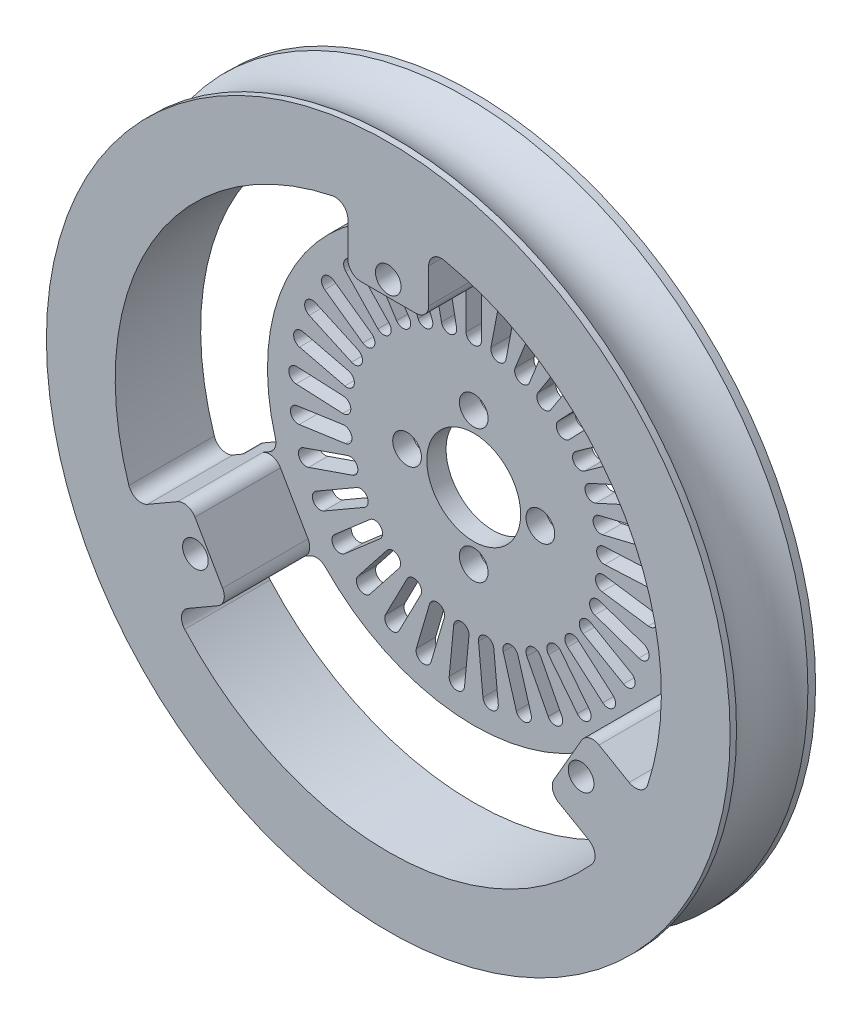
SolidWorks part; units mm, degrees
ref_plane "Plan de face" through (0, 0, 0) normal (0, 0, 1) x (1, 0, 0)
ref_plane "Plan de dessus" through (0, 0, 0) normal (0, 1, 0) x (1, 0, 0)
ref_plane "Plan de droite" through (0, 0, 0) normal (1, 0, 0) x (0, 0, -1)
sketch "Esquisse1" plane through (0, 0, 0) normal (0, 0, 1) x (1, 0, 0)
  circle A0 centre (0, 0) radius 33.8667
  dimension "D1" = 67.7333
extrude "Boss.-Extru.1" add sketch "Esquisse1" along normal blind 8.4667
sketch "Esquisse2" plane through (0, 0, 8.4667) normal (0, 0, 1) x (1, 0, 0)
  line L0 (4.0005, 25.2365) -> (4.0005, 21.8006)
  line L1 (2.7305, 20.5306) -> (-2.7305, 20.5306)
  line L2 (-4.0005, 21.8006) -> (-4.0005, 25.2365)
  line L3 (20.8801, -7.4357) -> (23.8557, -9.1537)
  line L4 (16.4147, -12.63) -> (19.1452, -7.9006)
  line L5 (19.8552, -16.0828) -> (16.8796, -14.3648)
  line L6 (-16.8796, -14.3648) -> (-19.8552, -16.0828)
  line L7 (-19.1452, -7.9006) -> (-16.4147, -12.63)
  line L8 (-23.8557, -9.1537) -> (-20.8801, -7.4357)
  arc A0 (-5.5301, 26.4797) -> (-25.6972, -8.4506) centre (0, 0) ccw
  arc A1 (4.0005, 21.8006) -> (2.7305, 20.5306) centre (2.7305, 21.8006) cw
  arc A2 (-2.7305, 20.5306) -> (-4.0005, 21.8006) centre (-2.7305, 21.8006) cw
  arc A3 (4.0005, 25.2365) -> (5.5301, 26.4797) centre (5.2705, 25.2365) cw
  arc A4 (-4.0005, 25.2365) -> (-5.5301, 26.4797) centre (-5.2705, 25.2365) ccw
  arc A5 (19.1452, -7.9006) -> (20.8801, -7.4357) centre (20.2451, -8.5356) cw
  arc A6 (16.8796, -14.3648) -> (16.4147, -12.63) centre (17.5146, -13.265) cw
  arc A7 (19.8552, -16.0828) -> (20.167, -18.0291) centre (19.2202, -17.1826) cw
  arc A8 (23.8557, -9.1537) -> (25.6972, -8.4506) centre (24.4907, -8.0539) ccw
  arc A9 (-16.4147, -12.63) -> (-16.8796, -14.3648) centre (-17.5146, -13.265) cw
  arc A10 (-20.8801, -7.4357) -> (-19.1452, -7.9006) centre (-20.2451, -8.5356) cw
  arc A11 (-23.8557, -9.1537) -> (-25.6972, -8.4506) centre (-24.4907, -8.0539) cw
  arc A12 (-19.8552, -16.0828) -> (-20.167, -18.0291) centre (-19.2202, -17.1826) ccw
  arc A13 (-20.167, -18.0291) -> (20.167, -18.0291) centre (0, 0) ccw
  arc A14 (25.6972, -8.4506) -> (5.5301, 26.4797) centre (0, 0) ccw
  point P5 (0, 20.5306)
  point P9 (4.0005, 20.5306)
  point P12 (-4.0005, 20.5306)
  point P15 (4.0005, 26.7536)
  point P45 (0, 0)
  dimension "D1" = 54.102
  dimension "D4" = 1.27
  dimension "D5" = 1.27
  dimension "D2" = 8.001
  dimension "D3" = 6.223
  dimension "D6" = 3
extrude "Enlèv. mat.-Extru.1" cut sketch "Esquisse2" against normal up to next
sketch "Esquisse7" plane through (0, 0, 0) normal (0, 1, 0) x (1, 0, 0)
  line L0 (0, -31.0899) -> (0, 31.0899) construction
  line L1 (-33.8667, 0) -> (-33.8667, -8.4667) construction
  line L2 (-33.8667, -0.762) -> (-33.8667, -7.8317)
  arc A0 (-33.8667, -7.8317) -> (-33.8667, -0.762) centre (-38.151, -4.2968) ccw
  point P0 (-32.5967, -4.2968)
  point P13 (0, 0)
  dimension "D1" = 0.635
  dimension "D2" = 1.27
  dimension "D3" = 0.762
revolve "Enlèvement de matière-Révolution4" cut sketch "Esquisse7" angle 360 about L0
sketch "Esquisse8" plane through (0, 0, 0) normal (0, 0, 1) x (1, 0, 0)
  line L0 (-22.7559, -8.5187) -> (-20.2341, -7.0628)
  line L1 (-18.7554, -15.4478) -> (-16.2336, -13.9919)
  line L2 (-16.4147, -12.63) -> (-19.1452, -7.9006) construction
  line L3 (-20.4902, -14.9829) -> (-23.2207, -10.2536)
  line L4 (4.0005, 23.9665) -> (4.0005, 21.0547)
  line L5 (-4.0005, 23.9665) -> (-4.0005, 21.0547)
  line L6 (-2.7305, 25.2365) -> (2.7305, 25.2365)
  line L7 (22.7559, -8.5187) -> (20.2341, -7.0628)
  line L8 (18.7554, -15.4478) -> (16.2336, -13.9919)
  line L9 (23.2207, -10.2536) -> (20.4902, -14.9829)
  line L10 (19.1452, -7.9006) -> (16.4147, -12.63) construction
  line L11 (-2.7305, 20.5306) -> (2.7305, 20.5306) construction
  arc A0 (-4.9621, 19.8227) -> (-19.648, -5.614) centre (0, 0) ccw
  arc A1 (-14.6859, -14.2086) -> (14.6859, -14.2086) centre (0, 0) ccw
  arc A2 (19.648, -5.614) -> (4.9621, 19.8227) centre (0, 0) ccw
  arc A3 (4.0005, 21.0547) -> (4.9621, 19.8227) centre (5.2705, 21.0547) ccw
  arc A4 (-4.0005, 21.0547) -> (-4.9621, 19.8227) centre (-5.2705, 21.0547) cw
  arc A5 (-20.2341, -7.0628) -> (-19.648, -5.614) centre (-20.8691, -5.9629) ccw
  arc A6 (-16.2336, -13.9919) -> (-14.6859, -14.2086) centre (-15.5986, -15.0917) cw
  arc A7 (16.2336, -13.9919) -> (14.6859, -14.2086) centre (15.5986, -15.0917) ccw
  arc A8 (20.2341, -7.0628) -> (19.648, -5.614) centre (20.8691, -5.9629) cw
  arc A9 (22.7559, -8.5187) -> (23.2207, -10.2536) centre (22.1209, -9.6186) cw
  arc A10 (18.7554, -15.4478) -> (20.4902, -14.9829) centre (19.3904, -14.3479) ccw
  arc A11 (-18.7554, -15.4478) -> (-20.4902, -14.9829) centre (-19.3904, -14.3479) cw
  arc A12 (-22.7559, -8.5187) -> (-23.2207, -10.2536) centre (-22.1209, -9.6186) ccw
  arc A13 (-4.0005, 23.9665) -> (-2.7305, 25.2365) centre (-2.7305, 23.9665) cw
  arc A14 (4.0005, 23.9665) -> (2.7305, 25.2365) centre (2.7305, 23.9665) ccw
  point P34 (-15.3539, -13.484)
  point P37 (15.3539, -13.484)
  point P40 (19.3544, -6.5549)
  point P43 (23.8557, -9.1537)
  point P46 (19.8552, -16.0828)
  point P49 (-19.8552, -16.0828)
  point P52 (-23.8557, -9.1537)
  point P55 (-4.0005, 25.2365)
  point P58 (4.0005, 25.2365)
  dimension "D1" = 20.4343
  dimension "D2" = 1.27
extrude "Boss.-Extru.2" add sketch "Esquisse8" against normal blind 1.905
sketch "Esquisse9" plane through (0, 0, -1.905) normal (0, 0, -1) x (-1, 0, 0)
  circle A0 centre (0, 0) radius 4.6482
  dimension "D1" = 9.2964
extrude "Enlèv. mat.-Extru.5" cut sketch "Esquisse9" against normal through all
sketch "Esquisse10" plane through (0, 0, 0) normal (0, 0, 1) x (1, 0, 0)
  circle A0 centre (0, 6.604) radius 1.4224
  circle A1 centre (6.604, 0) radius 1.4224
  circle A2 centre (0, -6.604) radius 1.4224
  circle A3 centre (-6.604, 0) radius 1.4224
  point P12 (0, 0)
  dimension "D1" = 2.8448
  dimension "D2" = 6.604
  dimension "D3" = 4
extrude "Enlèv. mat.-Extru.6" cut sketch "Esquisse10" against normal through all
sketch "Esquisse11" plane through (0, 0, -1.905) normal (0, 0, -1) x (-1, 0, 0)
  line L0 (-2.7305, 25.2365) -> (2.7305, 25.2365) construction
  circle A0 centre (0, 22.0615) radius 1.27
  circle A1 centre (19.1058, -11.0308) radius 1.27
  circle A2 centre (-19.1058, -11.0308) radius 1.27
  point P11 (0, 0)
  dimension "D1" = 2.54
  dimension "D2" = 3.175
  dimension "D3" = 3
extrude "Enlèv. mat.-Extru.7" cut sketch "Esquisse11" against normal through all
sketch "Esquisse12" plane through (0, 0, -1.905) normal (0, 0, -1) x (-1, 0, 0)
  line L0 (0, 17.5768) -> (0, 12.954) construction
  line L1 (0.762, 17.5768) -> (0.762, 12.954)
  line L2 (-0.762, 17.5768) -> (-0.762, 12.954)
  line L3 (3.3264, 17.2592) -> (2.4516, 12.7199) construction
  line L4 (4.0747, 17.115) -> (3.1998, 12.5757)
  line L5 (2.5782, 17.4034) -> (1.7033, 12.8641)
  line L6 (6.5326, 16.3177) -> (4.8145, 12.0261) construction
  line L7 (7.2401, 16.0345) -> (5.5219, 11.7429)
  line L8 (5.8252, 16.6009) -> (4.1071, 12.3093)
  line L9 (9.5027, 14.7865) -> (7.0035, 10.8976) construction
  line L10 (10.1438, 14.3746) -> (7.6445, 10.4856)
  line L11 (8.8617, 15.1985) -> (6.3624, 11.3096)
  line L12 (12.1294, 12.7209) -> (8.9393, 9.3753) construction
  line L13 (12.6809, 12.1951) -> (9.4908, 8.8494)
  line L14 (11.5779, 13.2468) -> (8.3878, 9.9011)
  line L15 (14.3176, 10.1955) -> (10.552, 7.5141) construction
  line L16 (14.7596, 9.5748) -> (10.994, 6.8934)
  line L17 (13.8756, 10.8163) -> (10.11, 8.1348)
  line L18 (15.9884, 7.3017) -> (11.7834, 5.3813) construction
  line L19 (16.305, 6.6085) -> (12.0999, 4.6881)
  line L20 (15.6719, 7.9948) -> (11.4668, 6.0744)
  line L21 (17.0813, 4.1439) -> (12.5888, 3.054) construction
  line L22 (17.261, 3.4034) -> (12.7685, 2.3135)
  line L23 (16.9017, 4.8844) -> (12.4092, 3.7945)
  line L24 (17.5569, 0.8363) -> (12.9393, 0.6164) construction
  line L25 (17.5931, 0.0752) -> (12.9756, -0.1448)
  line L26 (17.5206, 1.5975) -> (12.9031, 1.3775)
  line L27 (17.3979, -2.5014) -> (12.8221, -1.8435) construction
  line L28 (17.2894, -3.2557) -> (12.7137, -2.5978)
  line L29 (17.5063, -1.7472) -> (12.9306, -1.0893)
  line L30 (16.6101, -5.7488) -> (12.2415, -4.2368) construction
  line L31 (16.3609, -6.4689) -> (11.9923, -4.9569)
  line L32 (16.8593, -5.0287) -> (12.4908, -3.5167)
  line L33 (15.222, -8.7884) -> (11.2185, -6.477) construction
  line L34 (14.841, -9.4483) -> (10.8375, -7.1369)
  line L35 (15.603, -8.1285) -> (11.5995, -5.8171)
  line L36 (13.2837, -11.5104) -> (9.79, -8.4831) construction
  line L37 (12.7847, -12.0862) -> (9.291, -9.0589)
  line L38 (13.7827, -10.9345) -> (10.289, -7.9072)
  line L39 (10.8653, -13.8163) -> (8.0076, -10.1825) construction
  line L40 (10.2663, -14.2873) -> (7.4087, -10.6536)
  line L41 (11.4642, -13.3453) -> (8.6066, -9.7115)
  line L42 (8.0542, -15.6229) -> (5.9359, -11.514) construction
  line L43 (7.3769, -15.9721) -> (5.2586, -11.8631)
  line L44 (8.7314, -15.2737) -> (6.6132, -11.1648)
  line L45 (4.952, -16.8648) -> (3.6496, -12.4293) construction
  line L46 (4.2208, -17.0795) -> (2.9184, -12.644)
  line L47 (5.6831, -16.6501) -> (4.3807, -12.2146)
  line L48 (1.6708, -17.4972) -> (1.2314, -12.8953) construction
  line L49 (0.9122, -17.5696) -> (0.4728, -12.9678)
  line L50 (2.4293, -17.4248) -> (1.9899, -12.8229)
  line L51 (-1.6708, -17.4972) -> (-1.2314, -12.8953) construction
  line L52 (-2.4293, -17.4248) -> (-1.9899, -12.8229)
  line L53 (-0.9122, -17.5696) -> (-0.4728, -12.9678)
  line L54 (-4.952, -16.8648) -> (-3.6496, -12.4293) construction
  line L55 (-5.6831, -16.6501) -> (-4.3807, -12.2146)
  line L56 (-4.2208, -17.0795) -> (-2.9184, -12.644)
  line L57 (-8.0542, -15.6229) -> (-5.9359, -11.514) construction
  line L58 (-8.7314, -15.2737) -> (-6.6132, -11.1648)
  line L59 (-7.3769, -15.9721) -> (-5.2586, -11.8631)
  line L60 (-10.8653, -13.8163) -> (-8.0076, -10.1825) construction
  line L61 (-11.4642, -13.3453) -> (-8.6066, -9.7115)
  line L62 (-10.2663, -14.2873) -> (-7.4087, -10.6536)
  line L63 (-13.2837, -11.5104) -> (-9.79, -8.4831) construction
  line L64 (-13.7827, -10.9345) -> (-10.289, -7.9072)
  line L65 (-12.7847, -12.0862) -> (-9.291, -9.0589)
  line L66 (-15.222, -8.7884) -> (-11.2185, -6.477) construction
  line L67 (-15.603, -8.1285) -> (-11.5995, -5.8171)
  line L68 (-14.841, -9.4483) -> (-10.8375, -7.1369)
  line L69 (-16.6101, -5.7488) -> (-12.2415, -4.2368) construction
  line L70 (-16.8593, -5.0287) -> (-12.4908, -3.5167)
  line L71 (-16.3609, -6.4689) -> (-11.9923, -4.9569)
  line L72 (-17.3979, -2.5014) -> (-12.8221, -1.8435) construction
  line L73 (-17.5063, -1.7472) -> (-12.9306, -1.0893)
  line L74 (-17.2894, -3.2557) -> (-12.7137, -2.5978)
  line L75 (-17.5569, 0.8363) -> (-12.9393, 0.6164) construction
  line L76 (-17.5206, 1.5975) -> (-12.9031, 1.3775)
  line L77 (-17.5931, 0.0752) -> (-12.9756, -0.1448)
  line L78 (-17.0813, 4.1439) -> (-12.5888, 3.054) construction
  line L79 (-16.9017, 4.8844) -> (-12.4092, 3.7945)
  line L80 (-17.261, 3.4034) -> (-12.7685, 2.3135)
  line L81 (-15.9884, 7.3017) -> (-11.7834, 5.3813) construction
  line L82 (-15.6719, 7.9948) -> (-11.4668, 6.0744)
  line L83 (-16.305, 6.6085) -> (-12.0999, 4.6881)
  line L84 (-14.3176, 10.1955) -> (-10.552, 7.5141) construction
  line L85 (-13.8756, 10.8163) -> (-10.11, 8.1348)
  line L86 (-14.7596, 9.5748) -> (-10.994, 6.8934)
  line L87 (-12.1294, 12.7209) -> (-8.9393, 9.3753) construction
  line L88 (-11.5779, 13.2468) -> (-8.3878, 9.9011)
  line L89 (-12.6809, 12.1951) -> (-9.4908, 8.8494)
  line L90 (-9.5027, 14.7865) -> (-7.0035, 10.8976) construction
  line L91 (-8.8617, 15.1985) -> (-6.3624, 11.3096)
  line L92 (-10.1438, 14.3746) -> (-7.6445, 10.4856)
  line L93 (-6.5326, 16.3177) -> (-4.8145, 12.0261) construction
  line L94 (-5.8252, 16.6009) -> (-4.1071, 12.3093)
  line L95 (-7.2401, 16.0345) -> (-5.5219, 11.7429)
  line L96 (-3.3264, 17.2592) -> (-2.4516, 12.7199) construction
  line L97 (-2.5782, 17.4034) -> (-1.7033, 12.8641)
  line L98 (-4.0747, 17.115) -> (-3.1998, 12.5757)
  arc A0 (0.762, 17.5768) -> (-0.762, 17.5768) centre (0, 17.5768) ccw
  arc A1 (-0.762, 12.954) -> (0.762, 12.954) centre (0, 12.954) ccw
  arc A2 (4.0747, 17.115) -> (2.5782, 17.4034) centre (3.3264, 17.2592) ccw
  arc A3 (1.7033, 12.8641) -> (3.1998, 12.5757) centre (2.4516, 12.7199) ccw
  arc A4 (7.2401, 16.0345) -> (5.8252, 16.6009) centre (6.5326, 16.3177) ccw
  arc A5 (4.1071, 12.3093) -> (5.5219, 11.7429) centre (4.8145, 12.0261) ccw
  arc A6 (10.1438, 14.3746) -> (8.8617, 15.1985) centre (9.5027, 14.7865) ccw
  arc A7 (6.3624, 11.3096) -> (7.6445, 10.4856) centre (7.0035, 10.8976) ccw
  arc A8 (12.6809, 12.1951) -> (11.5779, 13.2468) centre (12.1294, 12.7209) ccw
  arc A9 (8.3878, 9.9011) -> (9.4908, 8.8494) centre (8.9393, 9.3753) ccw
  arc A10 (14.7596, 9.5748) -> (13.8756, 10.8163) centre (14.3176, 10.1955) ccw
  arc A11 (10.11, 8.1348) -> (10.994, 6.8934) centre (10.552, 7.5141) ccw
  arc A12 (16.305, 6.6085) -> (15.6719, 7.9948) centre (15.9884, 7.3017) ccw
  arc A13 (11.4668, 6.0744) -> (12.0999, 4.6881) centre (11.7834, 5.3813) ccw
  arc A14 (17.261, 3.4034) -> (16.9017, 4.8844) centre (17.0813, 4.1439) ccw
  arc A15 (12.4092, 3.7945) -> (12.7685, 2.3135) centre (12.5888, 3.054) ccw
  arc A16 (17.5931, 0.0752) -> (17.5206, 1.5975) centre (17.5569, 0.8363) ccw
  arc A17 (12.9031, 1.3775) -> (12.9756, -0.1448) centre (12.9393, 0.6164) ccw
  arc A18 (17.2894, -3.2557) -> (17.5063, -1.7472) centre (17.3979, -2.5014) ccw
  arc A19 (12.9306, -1.0893) -> (12.7137, -2.5978) centre (12.8221, -1.8435) ccw
  arc A20 (16.3609, -6.4689) -> (16.8593, -5.0287) centre (16.6101, -5.7488) ccw
  arc A21 (12.4908, -3.5167) -> (11.9923, -4.9569) centre (12.2415, -4.2368) ccw
  arc A22 (14.841, -9.4483) -> (15.603, -8.1285) centre (15.222, -8.7884) ccw
  arc A23 (11.5995, -5.8171) -> (10.8375, -7.1369) centre (11.2185, -6.477) ccw
  arc A24 (12.7847, -12.0862) -> (13.7827, -10.9345) centre (13.2837, -11.5104) ccw
  arc A25 (10.289, -7.9072) -> (9.291, -9.0589) centre (9.79, -8.4831) ccw
  arc A26 (10.2663, -14.2873) -> (11.4642, -13.3453) centre (10.8653, -13.8163) ccw
  arc A27 (8.6066, -9.7115) -> (7.4087, -10.6536) centre (8.0076, -10.1825) ccw
  arc A28 (7.3769, -15.9721) -> (8.7314, -15.2737) centre (8.0542, -15.6229) ccw
  arc A29 (6.6132, -11.1648) -> (5.2586, -11.8631) centre (5.9359, -11.514) ccw
  arc A30 (4.2208, -17.0795) -> (5.6831, -16.6501) centre (4.952, -16.8648) ccw
  arc A31 (4.3807, -12.2146) -> (2.9184, -12.644) centre (3.6496, -12.4293) ccw
  arc A32 (0.9122, -17.5696) -> (2.4293, -17.4248) centre (1.6708, -17.4972) ccw
  arc A33 (1.9899, -12.8229) -> (0.4728, -12.9678) centre (1.2314, -12.8953) ccw
  arc A34 (-2.4293, -17.4248) -> (-0.9122, -17.5696) centre (-1.6708, -17.4972) ccw
  arc A35 (-0.4728, -12.9678) -> (-1.9899, -12.8229) centre (-1.2314, -12.8953) ccw
  arc A36 (-5.6831, -16.6501) -> (-4.2208, -17.0795) centre (-4.952, -16.8648) ccw
  arc A37 (-2.9184, -12.644) -> (-4.3807, -12.2146) centre (-3.6496, -12.4293) ccw
  arc A38 (-8.7314, -15.2737) -> (-7.3769, -15.9721) centre (-8.0542, -15.6229) ccw
  arc A39 (-5.2586, -11.8631) -> (-6.6132, -11.1648) centre (-5.9359, -11.514) ccw
  arc A40 (-11.4642, -13.3453) -> (-10.2663, -14.2873) centre (-10.8653, -13.8163) ccw
  arc A41 (-7.4087, -10.6536) -> (-8.6066, -9.7115) centre (-8.0076, -10.1825) ccw
  arc A42 (-13.7827, -10.9345) -> (-12.7847, -12.0862) centre (-13.2837, -11.5104) ccw
  arc A43 (-9.291, -9.0589) -> (-10.289, -7.9072) centre (-9.79, -8.4831) ccw
  arc A44 (-15.603, -8.1285) -> (-14.841, -9.4483) centre (-15.222, -8.7884) ccw
  arc A45 (-10.8375, -7.1369) -> (-11.5995, -5.8171) centre (-11.2185, -6.477) ccw
  arc A46 (-16.8593, -5.0287) -> (-16.3609, -6.4689) centre (-16.6101, -5.7488) ccw
  arc A47 (-11.9923, -4.9569) -> (-12.4908, -3.5167) centre (-12.2415, -4.2368) ccw
  arc A48 (-17.5063, -1.7472) -> (-17.2894, -3.2557) centre (-17.3979, -2.5014) ccw
  arc A49 (-12.7137, -2.5978) -> (-12.9306, -1.0893) centre (-12.8221, -1.8435) ccw
  arc A50 (-17.5206, 1.5975) -> (-17.5931, 0.0752) centre (-17.5569, 0.8363) ccw
  arc A51 (-12.9756, -0.1448) -> (-12.9031, 1.3775) centre (-12.9393, 0.6164) ccw
  arc A52 (-16.9017, 4.8844) -> (-17.261, 3.4034) centre (-17.0813, 4.1439) ccw
  arc A53 (-12.7685, 2.3135) -> (-12.4092, 3.7945) centre (-12.5888, 3.054) ccw
  arc A54 (-15.6719, 7.9948) -> (-16.305, 6.6085) centre (-15.9884, 7.3017) ccw
  arc A55 (-12.0999, 4.6881) -> (-11.4668, 6.0744) centre (-11.7834, 5.3813) ccw
  arc A56 (-13.8756, 10.8163) -> (-14.7596, 9.5748) centre (-14.3176, 10.1955) ccw
  arc A57 (-10.994, 6.8934) -> (-10.11, 8.1348) centre (-10.552, 7.5141) ccw
  arc A58 (-11.5779, 13.2468) -> (-12.6809, 12.1951) centre (-12.1294, 12.7209) ccw
  arc A59 (-9.4908, 8.8494) -> (-8.3878, 9.9011) centre (-8.9393, 9.3753) ccw
  arc A60 (-8.8617, 15.1985) -> (-10.1438, 14.3746) centre (-9.5027, 14.7865) ccw
  arc A61 (-7.6445, 10.4856) -> (-6.3624, 11.3096) centre (-7.0035, 10.8976) ccw
  arc A62 (-5.8252, 16.6009) -> (-7.2401, 16.0345) centre (-6.5326, 16.3177) ccw
  arc A63 (-5.5219, 11.7429) -> (-4.1071, 12.3093) centre (-4.8145, 12.0261) ccw
  arc A64 (-2.5782, 17.4034) -> (-4.0747, 17.115) centre (-3.3264, 17.2592) ccw
  arc A65 (-3.1998, 12.5757) -> (-1.7033, 12.8641) centre (-2.4516, 12.7199) ccw
  point P3 (0, 15.2654)
  point P8 (0, 18.3388)
  point P9 (0, 12.192)
  point P10 (-0.762, 15.2654)
  point P16 (2.889, 14.9895)
  point P23 (5.6736, 14.1719)
  point P30 (8.2531, 12.8421)
  point P37 (10.5343, 11.0481)
  point P44 (12.4348, 8.8548)
  point P51 (13.8859, 6.3415)
  point P58 (14.8351, 3.599)
  point P65 (15.2481, 0.7264)
  point P72 (15.11, -2.1725)
  point P79 (14.4258, -4.9928)
  point P86 (13.2202, -7.6327)
  point P93 (11.5368, -9.9967)
  point P100 (9.4364, -11.9994)
  point P107 (6.995, -13.5684)
  point P114 (4.3008, -14.647)
  point P121 (1.4511, -15.1963)
  point P128 (-1.4511, -15.1963)
  point P135 (-4.3008, -14.647)
  point P142 (-6.995, -13.5684)
  point P149 (-9.4364, -11.9994)
  point P156 (-11.5368, -9.9967)
  point P163 (-13.2202, -7.6327)
  point P170 (-14.4258, -4.9928)
  point P177 (-15.11, -2.1725)
  point P184 (-15.2481, 0.7264)
  point P191 (-14.8351, 3.599)
  point P198 (-13.8859, 6.3415)
  point P205 (-12.4348, 8.8548)
  point P212 (-10.5343, 11.0481)
  point P219 (-8.2531, 12.8421)
  point P226 (-5.6736, 14.1719)
  point P233 (-2.889, 14.9895)
  point P238 (0, 0)
  dimension "D1" = 6.1468
  dimension "D2" = 1.524
  dimension "D3" = 12.192
  dimension "D4" = 33
extrude "Enlèv. mat.-Extru.8" cut sketch "Esquisse12" against normal through all
